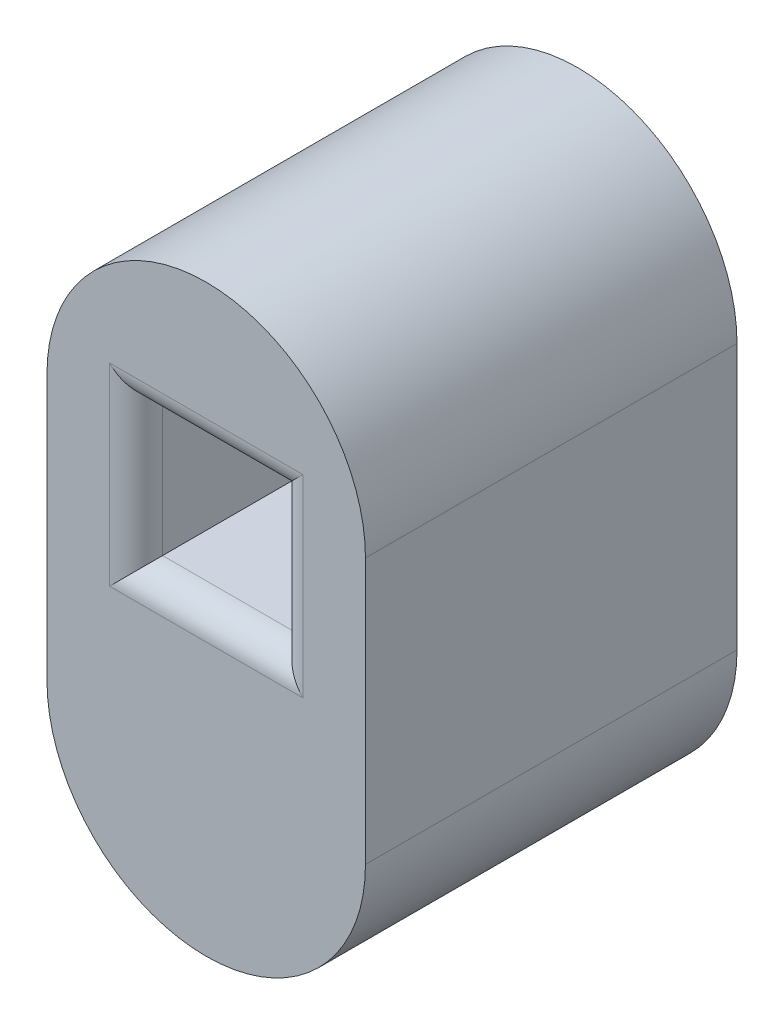
SolidWorks part; units mm, degrees
ref_plane "Front Plane" through (0, 0, 0) normal (0, 0, 1) x (1, 0, 0)
ref_plane "Top Plane" through (0, 0, 0) normal (0, 1, 0) x (1, 0, 0)
ref_plane "Right Plane" through (0, 0, 0) normal (1, 0, 0) x (0, 0, -1)
sketch "Sketch1" plane through (0, 0, 0) normal (0, 0, 1) x (1, 0, 0)
  line L0 (0, 0) -> (0, 10) construction
  line L1 (-6, 0) -> (-6, 10)
  line L2 (6, 0) -> (6, 10)
  line L4 (-2.644, 5.256) -> (2.644, 5.256)
  line L5 (-2.644, 5.256) -> (-2.644, 10.544)
  line L6 (-2.644, 10.544) -> (2.644, 10.544)
  line L7 (2.644, 5.256) -> (2.644, 10.544)
  line L8 (-2.644, 5.256) -> (2.644, 10.544) construction
  line L9 (-2.644, 10.544) -> (2.644, 5.256) construction
  arc A0 (-6, 0) -> (6, 0) centre (0, 0) ccw
  arc A1 (6, 10) -> (-6, 10) centre (0, 10) ccw
  point P3 (0, 5)
  point P8 (0, 7.9)
  dimension "D2" = 6
  dimension "D1" = 10
  dimension "D3" = 5.288
  dimension "D4" = 7.9
extrude "Boss-Extrude1" add sketch "Sketch1" along normal blind 14
fillet "Fillet1" radius 1 4 edges at (0, 5.256, 14) (-2.644, 7.9, 14) (0, 10.544, 14) (2.644, 7.9, 14)
fillet "Fillet2" radius 1 4 edges at (-2.644, 7.9, 0) (0, 5.256, 0) (2.644, 7.9, 0) (0, 10.544, 0)
